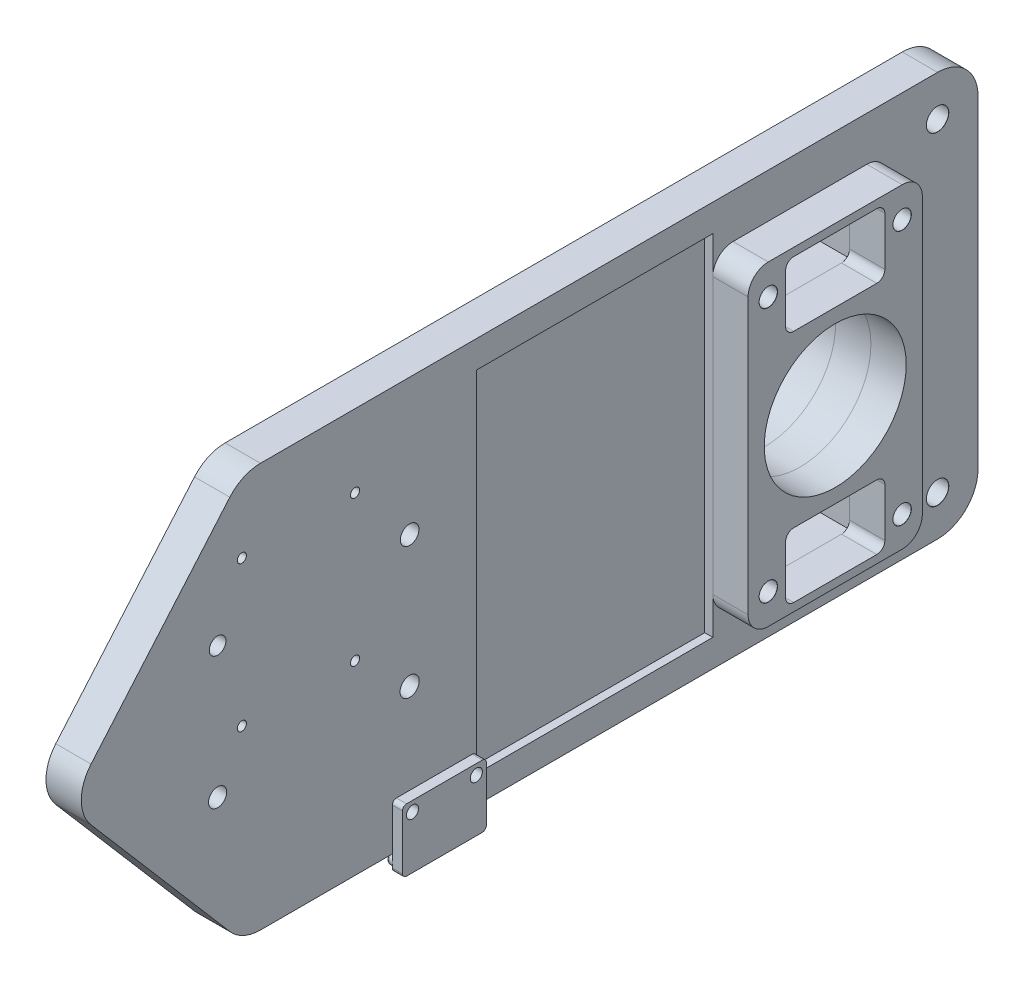
SolidWorks part; units mm, degrees
other "Bearing Plate"
other "Chassis"
other "Bearing Plate 2"
other "IMU"
material "Nylon 101"
ref_plane "Front Plane" through (0, 0, 0) normal (1, 0, 0) x (0, 1, 0)
ref_plane "Top Plane" through (0, 0, 0) normal (0, 0, 1) x (0, 1, 0)
ref_plane "Right Plane" through (0, 0, 0) normal (0, 1, 0) x (-1, 0, 0)
sketch "Sketch1" plane through (0, 0, 0) normal (1, 0, 0) x (0, 1, 0)
  line L0 (-50, 138.05) -> (-50, -44.05)
  line L1 (-50, -44.05) -> (50, -44.05)
  line L2 (50, -44.05) -> (50, 138.05)
  line L3 (50, 138.05) -> (0, 180.95)
  line L4 (0, 180.95) -> (-50, 138.05)
  line L5 (0, 180.95) -> (0, 0) construction
  line L6 (-50, 138.05) -> (0, 138.05) construction
  line L7 (0, 138.05) -> (50, 138.05) construction
  line L8 (-448.1018, -246.5596) -> (346.2414, -246.5596) construction
  line L9 (0, 77.55) -> (0, 138.05) construction
  line L10 (-40.75, 77.55) -> (40.75, 77.55)
  line L11 (-40.75, 77.55) -> (-40.75, 24.05)
  line L12 (-40.75, 24.05) -> (40.75, 24.05)
  line L13 (40.75, 77.55) -> (40.75, 24.05)
  line L14 (-40, -34.05) -> (40, -34.05) construction
  line L15 (-40, -24.05) -> (40, -24.05)
  line L16 (-40, -44.05) -> (40, -44.05)
  line L17 (0, -34.05) -> (0, 0) construction
  line L18 (-41, 98.35) -> (-41, 82.55) construction
  line L19 (-38.525, 100.825) -> (-38.525, 80.075)
  line L20 (-38.525, 100.825) -> (-54.025, 100.825)
  line L21 (-54.025, 100.825) -> (-54.025, 80.075)
  line L22 (-38.525, 80.075) -> (-54.025, 80.075)
  line L23 (-41, 90.45) -> (-54.025, 90.45) construction
  line L24 (-41, 100.825) -> (-41, 98.35) construction
  line L25 (-41, 98.35) -> (-38.525, 98.35) construction
  line L26 (-38.525, 80.075) -> (-38.525, 77.55) construction
  line L27 (-7, 124.05) -> (-4, 124.05) construction
  line L32 (-12.5, 149.05) -> (12.5, 149.05)
  line L33 (-12.5, 149.05) -> (-12.5, 89.05)
  line L34 (-12.5, 89.05) -> (12.5, 89.05)
  line L35 (12.5, 149.05) -> (12.5, 89.05)
  line L36 (-7, 140.55) -> (35, 140.55)
  line L37 (-7, 140.55) -> (-7, 107.55)
  line L38 (-7, 107.55) -> (35, 107.55)
  line L39 (35, 140.55) -> (35, 107.55)
  line L40 (-4, 138.05) -> (32, 138.05) construction
  line L41 (-4, 138.05) -> (-4, 110.05) construction
  line L42 (-4, 110.05) -> (32, 110.05) construction
  line L43 (32, 138.05) -> (32, 110.05) construction
  line L44 (14, 138.05) -> (14, 140.55) construction
  circle A0 centre (0, 0) radius 6.35 construction
  circle A1 centre (0, 0) radius 17.4625 construction
  circle A2 centre (0, 0) radius 19.05 construction
  circle A3 centre (0, 0) radius 17.5641
  arc A4 (-40, -24.05) -> (-40, -44.05) centre (-40, -34.05) ccw
  arc A5 (40, -44.05) -> (40, -24.05) centre (40, -34.05) ccw
  circle A6 centre (-41, 98.35) radius 1.5
  circle A7 centre (-41, 82.55) radius 1.5
  point P22 (0, -34.05)
  point P83 (0, 89.05)
  dimension "D5" = 12.7
  dimension "D6" = 34.925
  dimension "D8" = 38.1
  dimension "D9" = 0.1016
  dimension "D10" = 35.1282
  dimension "D14" = 10
  dimension "D3" = 5
  dimension "D15" = 5
  dimension "D18" = 3
  dimension "D20" = 7.5
  dimension "D25" = 36
  dimension "D30" = 8.5
  dimension "D27" = 30
  dimension "D28" = 15
  dimension "D29" = 5
  dimension "D4" = 100
  dimension "D7" = 246.5596
  dimension "D11" = 81.5
  dimension "D12" = 53.5
  dimension "D13" = 25
  dimension "D16" = 15.5
  dimension "D17" = 20.75
  dimension "D19" = 15.8
  dimension "D21" = 60
  dimension "D22" = 225
  dimension "D23" = 42
  dimension "D24" = 33
  dimension "D26" = 28
extrude "Boss-Extrude1" add sketch "Sketch1" along normal mid plane 8.7312
sketch "Sketch2" plane through (4.3656, 0, 0) normal (1, 0, 0) x (0, 1, 0)
  line L0 (-39.05, 0) -> (-19.05, 0) construction
  line L1 (-39.05, 21.55) -> (39.05, 21.55)
  line L2 (-39.05, 21.55) -> (-39.05, -21.55)
  line L3 (-39.05, -21.55) -> (39.05, -21.55)
  line L4 (39.05, 21.55) -> (39.05, -21.55)
  line L5 (19.05, 0) -> (39.05, 0) construction
  line L6 (-31.55, 16.55) -> (31.55, 16.55) construction
  line L7 (31.55, 16.55) -> (31.55, -16.55) construction
  line L8 (31.55, -16.55) -> (-31.55, -16.55) construction
  line L9 (-31.55, -16.55) -> (-31.55, 16.55) construction
  line L10 (0, 16.55) -> (0, 21.55) construction
  line L11 (31.55, 0) -> (39.05, 0) construction
  line L12 (-31.55, 24.05) -> (-31.55, 16.55) construction
  line L13 (-31.55, 16.55) -> (-39.05, 16.55) construction
  line L14 (-40.75, 24.05) -> (40.75, 24.05) construction
  circle A1 centre (0, 0) radius 19.05 construction
  circle A2 centre (-31.55, 16.55) radius 2 construction
  circle A3 centre (-31.55, -16.55) radius 2 construction
  circle A4 centre (31.55, 16.55) radius 2 construction
  circle A5 centre (31.55, -16.55) radius 2 construction
  dimension "D1" = 20
  dimension "D3" = 4
  dimension "D2" = 7.5
  dimension "D4" = 2.5
extrude "Boss-Extrude2" add sketch "Sketch2" along normal blind 8.7312 separate body
sketch "Sketch3" plane through (13.0969, 0, 0) normal (1, 0, 0) x (0, 1, 0)
  circle A0 centre (0, 0) radius 17.5641 construction
  circle A1 centre (0, 0) radius 17.5641
hole_wizard "M4 Clearance Hole2" positions "Sketch22" profile "Sketch23" hole size "M4" standard "ANSI Metric" end condition through all
sketch "Sketch22" plane through (13.0969, 0, 0) normal (1, 0, 0) x (0, 1, 0)
  point P0 (-31.55, 16.55)
  point P3 (-31.55, -16.55)
  point P6 (31.55, -16.55)
  point P9 (31.55, 16.55)
sketch "Sketch23" plane through (13.0969, -31.55, 16.55) normal (0, 1, 0) x (0, 0, -1)
  line L0 (0, 0) -> (0, 17.4625)
  line L1 (0, 17.4625) -> (2.25, 17.4625)
  line L2 (2.25, 17.4625) -> (2.25, 0.025)
  line L3 (2.25, 0.025) -> (2.275, 0)
  line L5 (2.275, 0) -> (0, 0)
  line L6 (-2.25, 0.025) -> (-2.275, 0) construction
  line L11 (0, -6.35) -> (0, 107.95) construction
  dimension "Thru Hole Dia." = 4.5
  dimension "Thru Hole Depth" = 17.4625
  dimension "Near C'Sink Dia." = 4.55
  dimension "Near C'Sink Angle" = 90
sketch "Sketch24" plane through (-4.3656, 0, 0) normal (-1, 0, 0) x (0, -1, 0)
  line L0 (39.05, 21.55) -> (39.05, -21.55) construction
  line L1 (39.05, -21.55) -> (-39.05, -21.55) construction
  line L2 (-39.05, 21.55) -> (-39.05, -21.55) construction
  line L3 (39.05, 21.55) -> (-39.05, 21.55) construction
  line L4 (39.05, 21.55) -> (39.05, -21.55)
  line L5 (39.05, -21.55) -> (-39.05, -21.55)
  line L6 (-39.05, 21.55) -> (-39.05, -21.55)
  line L7 (39.05, 21.55) -> (-39.05, 21.55)
extrude "Boss-Extrude3" add sketch "Sketch24" along normal blind 8.7312 separate body
hole_wizard "Tap Drill for M4x0.7 Tap1" positions "Sketch25" profile "Sketch27" hole size "M4x0.7" standard "ANSI Metric"
sketch "Sketch25" plane through (-13.0969, 0, 0) normal (-1, 0, 0) x (0, -1, 0)
  point P0 (-31.55, 16.55)
  point P2 (-31.55, -16.55)
  point P4 (31.55, -16.55)
  point P6 (31.55, 16.55)
sketch "Sketch27" plane through (-13.0969, 31.55, 16.55) normal (0, 1, 0) x (0, 0, 1)
  line L0 (0, 0) -> (0, 9.7227)
  line L1 (0, 9.7227) -> (1.65, 8.7312)
  line L2 (1.65, 8.7312) -> (1.65, 0.025)
  line L3 (1.65, 0.025) -> (1.675, 0)
  line L5 (1.675, 0) -> (0, 0)
  line L6 (-1.65, 0.025) -> (-1.675, 0) construction
  line L10 (0, 9.7227) -> (-1.65, 8.7312) construction
  line L11 (0, -6.35) -> (0, 107.95) construction
  dimension "Hole Dia." = 3.3
  dimension "Hole Depth" = 8.7312
  dimension "Near C'Sink Dia." = 3.35
  dimension "Near C'Sink Angle" = 90
  dimension "Drill Angle" = 118
hole_wizard "Tap Drill for M3x0.5 Tap1" positions "Sketch9" profile "Sketch10" hole size "M3x0.5" standard "ANSI Metric" end condition through all
sketch "Sketch9" plane through (4.3656, 0, 0) normal (1, 0, 0) x (0, 1, 0)
  point P0 (-41, 98.35)
  point P3 (-41, 82.55)
sketch "Sketch10" plane through (4.3656, -41, 98.35) normal (0, 1, 0) x (0, 0, -1)
  line L0 (0, 0) -> (0, 17.4625)
  line L1 (0, 17.4625) -> (1.25, 17.4625)
  line L2 (1.25, 17.4625) -> (1.25, 0.025)
  line L3 (1.25, 0.025) -> (1.275, 0)
  line L5 (1.275, 0) -> (0, 0)
  line L6 (-1.25, 0.025) -> (-1.275, 0) construction
  line L11 (0, -6.35) -> (0, 107.95) construction
  dimension "Thru Hole Dia." = 2.5
  dimension "Thru Hole Depth" = 17.4625
  dimension "Near C'Sink Dia." = 2.55
  dimension "Near C'Sink Angle" = 90
extrude "Cut-Extrude3" cut sketch "Sketch3" against normal through all
hole_wizard "M5 Clearance Hole1" positions "Sketch13" profile "Sketch12" hole size "M5" standard "ANSI Metric" end condition through all
sketch "Sketch13" plane through (4.3656, 0, 0) normal (1, 0, 0) x (0, 1, 0)
  point P0 (-40, -34.05)
  point P3 (40, -34.05)
sketch "Sketch12" plane through (4.3656, -40, -34.05) normal (0, 1, 0) x (0, 0, -1)
  line L0 (0, 0) -> (0, 17.4625)
  line L1 (0, 17.4625) -> (2.75, 17.4625)
  line L2 (2.75, 17.4625) -> (2.75, 0.025)
  line L3 (2.75, 0.025) -> (2.775, 0)
  line L5 (2.775, 0) -> (0, 0)
  line L6 (-2.75, 0.025) -> (-2.775, 0) construction
  line L11 (0, -6.35) -> (0, 107.95) construction
  dimension "Thru Hole Dia." = 5.5
  dimension "Thru Hole Depth" = 17.4625
  dimension "Near C'Sink Dia." = 5.55
  dimension "Near C'Sink Angle" = 90
sketch "Sketch14" plane through (4.3656, 0, 0) normal (1, 0, 0) x (0, 1, 0)
  line L8 (43.25, 21.55) -> (43.25, 80.05)
  line L9 (-43.25, 21.55) -> (43.25, 21.55)
  line L10 (-43.25, 80.05) -> (-43.25, 21.55)
  line L11 (43.25, 80.05) -> (-43.25, 80.05)
  line L12 (43.25, 21.55) -> (43.25, 80.05)
  line L13 (-43.25, 21.55) -> (43.25, 21.55)
  line L14 (-43.25, 80.05) -> (-43.25, 21.55)
  line L15 (43.25, 80.05) -> (-43.25, 80.05)
  dimension "D1" = 2.5
extrude "Cut-Extrude4" cut sketch "Sketch14" against normal blind 2
fillet "Fillet4" radius 10 5 edges at (0, 50, -44.05) (0, -50, -44.05) (0, 50, 138.05) (0, 0, 180.95) (0, -50, 138.05)
fillet "Fillet5" radius 5 4 edges at (-8.7312, -39.05, 21.55) (-8.7312, -39.05, -21.55) (-8.7312, 39.05, -21.55) (-8.7312, 39.05, 21.55)
fillet "Fillet6" radius 5 4 edges at (8.7312, -39.05, 21.55) (8.7312, 39.05, -21.55) (8.7312, -39.05, -21.55) (8.7312, 39.05, 21.55)
sketch "Sketch28" plane through (4.3656, 0, 0) normal (1, 0, 0) x (0, 1, 0)
  line L0 (-38.525, 100.825) -> (-54.025, 100.825) construction
  line L1 (-38.525, 100.825) -> (-54.025, 100.825)
  line L2 (-54.025, 100.825) -> (-54.025, 80.075) construction
  line L3 (-54.025, 100.825) -> (-54.025, 80.075)
  line L4 (-38.525, 100.825) -> (-38.525, 80.075) construction
  line L5 (-38.525, 100.825) -> (-38.525, 80.075)
  line L6 (-38.525, 80.075) -> (-54.025, 80.075) construction
  line L7 (-38.525, 80.075) -> (-54.025, 80.075)
  circle A0 centre (-41, 82.55) radius 1.5 construction
  circle A1 centre (-41, 82.55) radius 1.5
  circle A2 centre (-41, 98.35) radius 1.5 construction
  circle A3 centre (-41, 98.35) radius 1.5
extrude "Boss-Extrude4" add sketch "Sketch28" along normal blind 2.5 separate body
fillet "Fillet7" radius 1 4 edges at (5.6156, -38.525, 100.825) (5.6156, -38.525, 80.075) (5.6156, -54.025, 80.075) (5.6156, -54.025, 100.825)
sketch "Sketch29" plane through (4.3656, 0, 0) normal (-1, 0, 0) x (0, -1, 0)
  line L0 (52.025, 100.825) -> (52.025, 80.075) construction
  line L1 (52.025, 90.45) -> (54.025, 90.45) construction
  line L3 (53.025, 80.075) -> (39.525, 80.075) construction
  line L4 (54.025, 99.825) -> (54.025, 81.075) construction
  line L6 (52.025, 80.2) -> (52.025, 80.075) construction
  line L8 (52.025, 100.825) -> (52.025, 100.7) construction
  circle A6 centre (52.025, 99.2) radius 1.5
  circle A7 centre (52.025, 95.7) radius 1.5
  circle A8 centre (52.025, 92.2) radius 1.5
  circle A9 centre (52.025, 88.7) radius 1.5
  circle A10 centre (52.025, 85.2) radius 1.5
  circle A11 centre (52.025, 81.7) radius 1.5
  dimension "D3" = 6
  dimension "D2" = 3
  dimension "D4" = 0.5
  dimension "D1" = 2
extrude "Boss-Extrude5" add sketch "Sketch29" along normal blind 1.5
fillet "Fillet8" radius 0.5 6 edges at (2.8656, -52.025, 83.2) (2.8656, -52.025, 86.7) (2.8656, -52.025, 90.2) (2.8656, -52.025, 93.7) (2.8656, -52.025, 97.2) (2.8656, -52.025, 100.7)
hole_wizard "Tap Drill for #4-40 Tap1" positions "Sketch33" profile "Sketch34" hole size "#4-40" standard "ANSI Inch" end condition through all
sketch "Sketch33" plane through (4.3656, 0, 0) normal (1, 0, 0) x (0, 1, 0)
  point P0 (-4, 138.05)
  point P3 (-4, 110.05)
  point P6 (32, 110.05)
  point P9 (32, 138.05)
sketch "Sketch34" plane through (4.3656, -4, 138.05) normal (0, 1, 0) x (0, 0, -1)
  line L0 (0, 0) -> (0, 17.4625)
  line L1 (0, 17.4625) -> (1.1303, 17.4625)
  line L2 (1.1303, 17.4625) -> (1.1303, 0)
  line L5 (1.1303, 0) -> (0, 0)
  line L11 (0, -6.35) -> (0, 107.95) construction
  dimension "Thru Hole Dia." = 2.2606
  dimension "Thru Hole Depth" = 17.4625
sketch "Sketch35" plane through (4.3656, 0, 0) normal (1, 0, 0) x (0, 1, 0)
  line L0 (-16.25, 144.05) -> (16.25, 144.05) construction
  line L1 (0, 180.95) -> (0, 0) construction
  line L2 (-16.25, 144.05) -> (-16.25, 96.55) construction
  line L3 (16.25, 144.05) -> (16.25, 96.55) construction
  line L4 (-16.25, 96.55) -> (16.25, 96.55) construction
  line L5 (-12.5, 149.05) -> (12.5, 149.05) construction
  line L6 (-12.5, 89.05) -> (12.5, 89.05) construction
  circle A0 centre (-16.25, 144.05) radius 2.25
  circle A1 centre (16.25, 144.05) radius 2.065
  circle A2 centre (-16.25, 96.55) radius 2.3737
  circle A3 centre (16.25, 96.55) radius 2.3096
  point P9 (0, 144.05)
  dimension "D1" = 4.5
  dimension "D2" = 32.5
  dimension "D3" = 5
  dimension "D4" = 7.5
extrude "Cut-Extrude5" cut sketch "Sketch35" against normal through all
sketch "Sketch36" plane through (13.0969, 0, 0) normal (1, 0, 0) x (0, 1, 0)
  line L0 (-39.05, 16.55) -> (-39.05, -16.55) construction
  line L1 (-37.05, 12.275) -> (-21.05, 12.275)
  line L2 (-37.05, 12.275) -> (-37.05, -12.275)
  line L3 (-37.05, -12.275) -> (-21.05, -12.275)
  line L4 (-21.05, 12.275) -> (-21.05, -12.275)
  line L5 (0, 0) -> (0, 21.55) construction
  line L6 (34.05, 21.55) -> (-34.05, 21.55) construction
  line L7 (21.05, 12.275) -> (21.05, -12.275)
  line L8 (37.05, -12.275) -> (21.05, -12.275)
  line L9 (37.05, 12.275) -> (37.05, -12.275)
  line L10 (37.05, 12.275) -> (21.05, 12.275)
  circle A1 centre (0, 0) radius 19.05 construction
  circle A3 centre (-31.55, 16.55) radius 2.275 construction
  circle A5 centre (-31.55, -16.55) radius 2.275 construction
  dimension "D1" = 2
  dimension "D2" = 2
  dimension "D3" = 2
  dimension "D4" = 2
extrude "Cut-Extrude6" cut sketch "Sketch36" against normal through all
fillet "Fillet9" radius 2 8 edges at (8.7312, -37.05, 12.275) (8.7312, 21.05, -12.275) (8.7312, 37.05, -12.275) (8.7312, 37.05, 12.275) (8.7312, 21.05, 12.275) (8.7312, -21.05, -12.275) (8.7312, -37.05, -12.275) (8.7312, -21.05, 12.275)
fillet "Fillet10" radius 2 8 edges at (-8.7313, -21.05, 12.275) (-8.7313, -21.05, -12.275) (-8.7313, -37.05, -12.275) (-8.7313, -37.05, 12.275) (-8.7313, 37.05, -12.275) (-8.7313, 21.05, -12.275) (-8.7313, 21.05, 12.275) (-8.7313, 37.05, 12.275)
